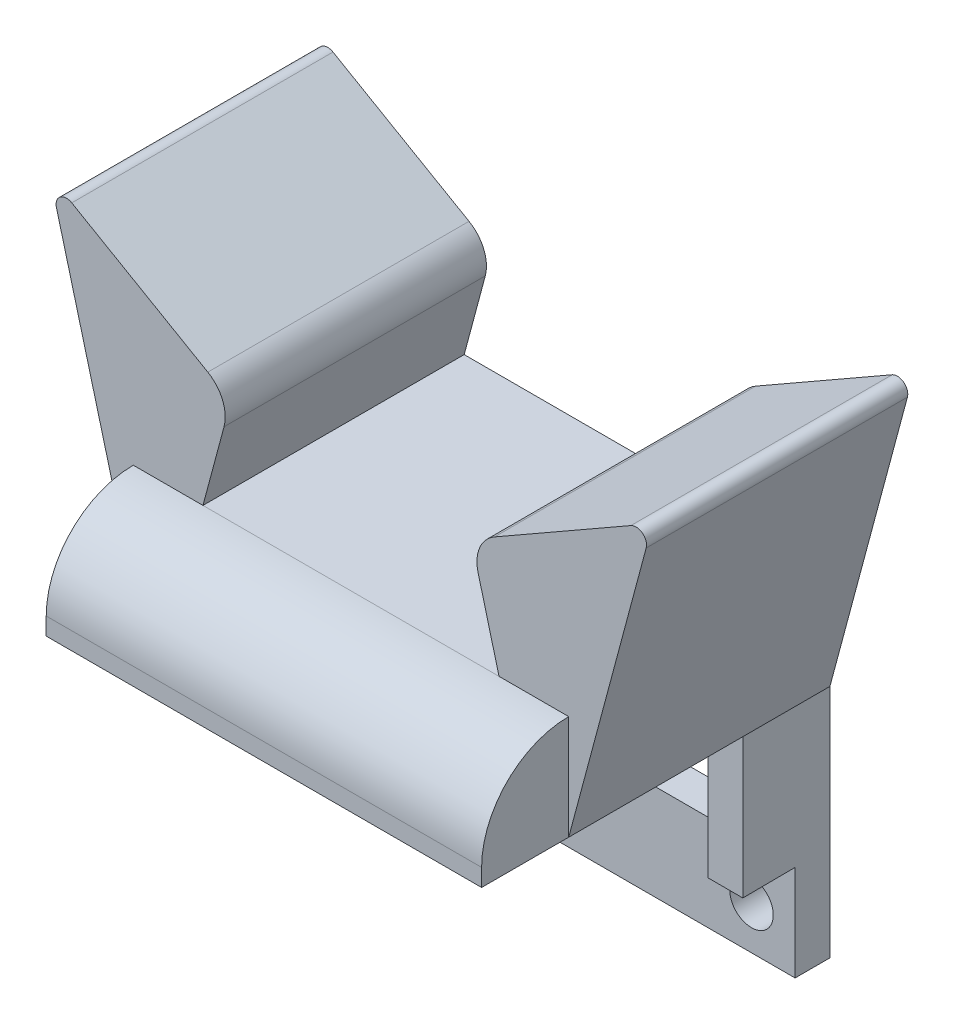
SolidWorks part; units mm, degrees
ref_plane "Front Plane" through (0, 0, 0) normal (0, 0, 1) x (1, 0, 0)
ref_plane "Top Plane" through (0, 0, 0) normal (0, 1, 0) x (1, 0, 0)
ref_plane "Right Plane" through (0, 0, 0) normal (1, 0, 0) x (0, 0, -1)
sketch "Sketch1" plane through (0, 0, 0) normal (0, 0, 1) x (1, 0, 0)
  line L0 (-2, 2) -> (-2, -6)
  line L1 (0, 0) -> (21, 0)
  line L2 (0, 0) -> (0, -4)
  line L3 (0, -4) -> (21, -4)
  line L4 (21, 0) -> (21, -4)
  line L5 (-2, -6) -> (23, -6)
  line L6 (23, 2) -> (23, -6)
  line L7 (-2, 2) -> (23, 2)
  line L8 (23, -4) -> (-2, -4)
  line L9 (0, -4) -> (0, -6)
  line L10 (0, -6) -> (21, -6)
  line L11 (21, -6) -> (21, -4)
  dimension "D1" = 21
  dimension "D2" = 4
  dimension "D3" = 2
extrude "Boss-Extrude1" add sketch "Sketch1" along normal blind 16 contours L8 L6 L7 L0 L2 L1 L4
sketch "Sketch3" plane through (0, 0, 16) normal (0, 0, 1) x (1, 0, 0)
  line L0 (-2, 2) -> (-2, -4)
  line L1 (-2, -4) -> (23, -4)
  line L2 (23, -4) -> (23, 2)
  line L3 (23, 2) -> (-2, 2)
extrude "Boss-Extrude2" add sketch "Sketch3" along normal blind 2
sketch "Sketch6" plane through (0, 0, 0) normal (0, 0, -1) x (-1, 0, 0)
  line L0 (2, 2) -> (2, -4) construction
  line L1 (-23, 2) -> (2, 2)
  line L2 (-23, 2) -> (-23, -13)
  line L3 (-23, -13) -> (2, -13)
  line L4 (2, 2) -> (2, -13)
  line L5 (0, 0) -> (-21, 0) construction
  dimension "D1" = 0
  dimension "D2" = 13
extrude "Boss-Extrude3" add sketch "Sketch6" along normal blind 2
sketch "Sketch7" plane through (0, 0, -2) normal (0, 0, -1) x (-1, 0, 0)
  line L0 (-23, 2) -> (-23, -13) construction
  line L1 (2, -13) -> (2, 2) construction
  line L2 (-21, -4) -> (0, -4)
  line L3 (-21, -4) -> (-21, -12)
  line L4 (-21, -12) -> (0, -12)
  line L5 (0, -4) -> (0, -12)
  line L6 (2, 2) -> (-23, 2) construction
  dimension "D1" = 2
  dimension "D2" = 2
  dimension "D3" = 6
  dimension "D4" = 8
extrude "Cut-Extrude1" cut sketch "Sketch7" against normal blind 2
sketch "Sketch10" plane through (0, 0, -2) normal (0, 0, -1) x (-1, 0, 0)
  line L1 (-23, -13) -> (2, -13)
  line L2 (-23, -13) -> (-23, -17.5)
  line L3 (-23, -17.5) -> (2, -17.5)
  line L4 (2, -13) -> (2, -17.5)
  dimension "D1" = 4.5
extrude "Boss-Extrude4" add sketch "Sketch10" against normal blind 2
sketch "Sketch11" plane through (0, 0, -2) normal (0, 0, -1) x (-1, 0, 0)
  line L0 (-21, -12) -> (0, -17.5)
  line L1 (0, -12) -> (-21, -17.5)
  line L2 (-23, -17.5) -> (2, -17.5) construction
  line L3 (-21, -12) -> (0, -12)
  line L4 (-21, -12) -> (-21, -17.5)
  line L5 (-21, -17.5) -> (0, -17.5)
  line L6 (0, -12) -> (0, -17.5)
  line L7 (-23, 2) -> (-23, -17.5) construction
  circle A0 centre (-20.4969, -15) radius 1.25
  circle A1 centre (-0.4969, -15) radius 1.25
  point P11 (-10.5, -14.75)
  dimension "D1" = 2.5
  dimension "D2" = 2.5
  dimension "D5" = 2.5
  dimension "D3" = 10
  dimension "D4" = 20
extrude "Cut-Extrude2" cut sketch "Sketch11" against normal blind 3 contours L4 A0 | L4 A0 | L6 A1 | L6 A1
fillet "Fillet1" radius 5 1 edges at (10.5, 2, 18)
sketch "Sketch13" plane through (0, 0, -2) normal (0, 0, -1) x (-1, 0, 0)
  line L0 (-21, -4) -> (-23, -4)
  line L1 (-23, -4) -> (-27.8231, 14)
  line L2 (-27.8231, 14) -> (-17.407, 8.0414)
  line L3 (-17.407, 8.0414) -> (-19, 2)
  line L4 (2, 2) -> (-23, 2) construction
  line L5 (-19, 2) -> (-2, 2)
  line L6 (-2, 2) -> (-3.6077, 8)
  line L7 (-3.6077, 8) -> (6.7846, 14)
  line L8 (2, -4) -> (6.7846, 14)
  line L11 (-23, 2) -> (-23, -17.5) construction
  line L12 (0, -4) -> (2, -4)
  line L14 (-22.2327, -3) -> (-26.2358, 11.9399)
  line L15 (-26.2358, 11.9399) -> (-18.5696, 7.5544)
  line L16 (-18.5696, 7.5544) -> (-20.2979, 1)
  line L17 (-20.2979, 1) -> (-0.6968, 1)
  line L18 (-21, -4) -> (-21, -12)
  line L19 (0, -4) -> (-21, -4)
  line L20 (0, -12) -> (0, -4)
  line L21 (-21, -12) -> (0, -12)
  line L23 (0, -4) -> (-21, -4)
  line L26 (-0.6968, 1) -> (-2.4432, 7.5176)
  line L27 (-2.4432, 7.5176) -> (5.1997, 11.9303)
  line L28 (1.2311, -3) -> (5.1997, 11.9303)
  line L29 (0, -3) -> (1.2311, -3)
  line L30 (0, -3) -> (-21, -3)
  line L31 (-21, -3) -> (-22.2327, -3)
  dimension "D1" = 105
  dimension "D2" = 105
  dimension "D3" = 12
  dimension "D4" = 12
  dimension "D5" = 18
  dimension "D6" = 18
  dimension "D7" = 4
  dimension "D8" = 4
  dimension "D9" = 0
  dimension "D10" = 15
  dimension "D11" = 45.228
  dimension "D12" = 1
extrude "Boss-Extrude7" add sketch "Sketch13" against normal blind 15
sketch "Sketch14" plane through (0, 0, -2) normal (0, 0, -1) x (-1, 0, 0)
  line L0 (-27.8231, 14) -> (-23, -4)
  line L1 (-23, -4) -> (-19, 2)
  line L2 (-19, 2) -> (-17.407, 8.0414)
  line L3 (-17.407, 8.0414) -> (-27.8231, 14)
  line L4 (-2, 2) -> (2, -4)
  line L5 (2, -4) -> (6.7846, 14)
  line L6 (6.7846, 14) -> (-3.6077, 8)
  line L7 (-3.6077, 8) -> (-2, 2)
extrude "Boss-Extrude8" add sketch "Sketch14" against normal blind 2
sketch "Sketch15" plane through (0, 0, 13) normal (0, 0, 1) x (1, 0, 0)
  line L0 (-6.7846, 14) -> (-2, -4)
  line L1 (-2, -4) -> (2, 2)
  line L2 (2, 2) -> (3.6077, 8)
  line L3 (3.6077, 8) -> (-6.7846, 14)
  line L4 (19, 2) -> (23, -4)
  line L5 (23, -4) -> (27.8231, 14)
  line L6 (27.8231, 14) -> (17.407, 8.0414)
  line L7 (17.407, 8.0414) -> (19, 2)
extrude "Boss-Extrude9" add sketch "Sketch15" against normal blind 2
fillet "Fillet4" radius 2 2 edges at (17.407, 8.0414, 5.5) (3.6077, 8, 5.5)
fillet "Fillet5" radius 0.6 2 edges at (27.8231, 14, 5.5) (-6.7846, 14, 5.5)
sketch "Sketch16" plane through (-2, 0, 0) normal (-1, 0, 0) x (0, 0, 1)
  line L0 (0, -4) -> (0, -12.0201)
  line L1 (0, -17.5) -> (0, -4) construction
  line L2 (0, -12.0201) -> (3, -12.0201)
  line L3 (3, -12.0201) -> (3, -4)
  line L4 (13, -4) -> (0, -4) construction
  line L5 (3, -4) -> (0, -4)
  dimension "D1" = 3
extrude "Boss-Extrude10" add sketch "Sketch16" against normal up to surface (2 mm away) up to face at (0, -8, -1)
sketch "Sketch17" plane through (23, 0, 0) normal (1, 0, 0) x (0, 0, -1)
  line L0 (0, -12) -> (-3, -12.0201)
  line L1 (-3, -12.0201) -> (-3, -4)
  line L2 (-3, -4) -> (0, -4)
  line L3 (0, -4) -> (0, -12)
extrude "Boss-Extrude11" add sketch "Sketch17" against normal up to surface (2 mm away) up to face at (21, -8, -1)
sketch "Sketch18" plane through (0, -4, 0) normal (0, -1, 0) x (1, 0, 0)
  line L1 (0, 13) -> (21, 13)
  line L2 (0, 13) -> (0, 0)
  line L3 (0, 0) -> (21, 0)
  line L4 (21, 13) -> (21, 0)
extrude "Cut-Extrude3" cut sketch "Sketch18" against normal up to surface (4 mm away) up to face at (10.5, 0, 10.6667)
